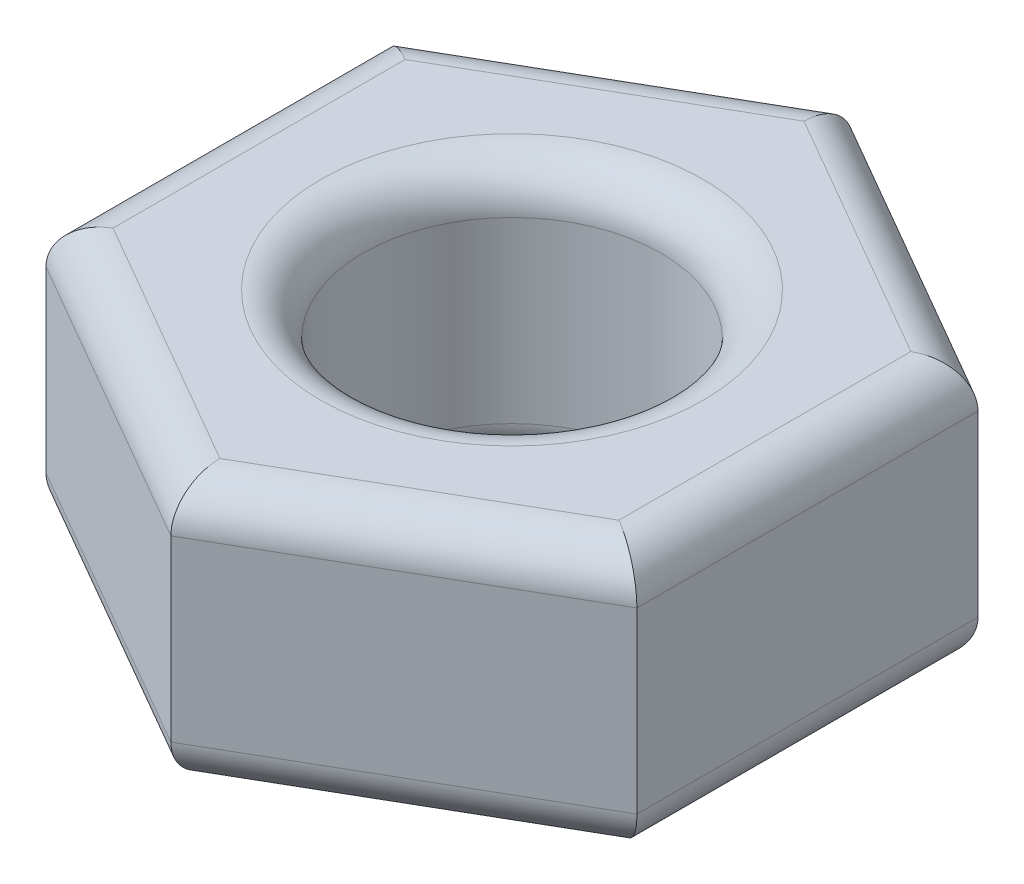
SolidWorks part; units mm, degrees
ref_plane "Front Plane" through (0, 0, 0) normal (0, 0, 1) x (1, 0, 0)
ref_plane "Top Plane" through (0, 0, 0) normal (0, 1, 0) x (1, 0, 0)
ref_plane "Right Plane" through (0, 0, 0) normal (1, 0, 0) x (0, 0, -1)
sketch "Sketch1" plane through (0, 0, 0) normal (0, 1, 0) x (1, 0, 0)
  line L0 (0, 4.0126) -> (0, -4.0126) construction
  line L1 (0, -4.0126) -> (3.475, -2.0063)
  line L2 (3.475, -2.0063) -> (3.475, 2.0063)
  line L3 (3.475, 2.0063) -> (0, 4.0126)
  line L4 (0, 4.0126) -> (-3.475, 2.0063)
  line L5 (-3.475, 2.0063) -> (-3.475, -2.0063)
  line L6 (-3.475, -2.0063) -> (0, -4.0126)
  circle A0 centre (0, 0) radius 3.475 construction
  circle A1 centre (0, 0) radius 1.75
  dimension "D2" = 3.5
  dimension "D1" = 6.95
extrude "Boss-Extrude2" add sketch "Sketch1" along normal blind 3.1
fillet "Fillet1" radius 0.5 14 edges at (1.7375, 3.1, -3.0094) (-1.7375, 3.1, -3.0094) (-3.475, 3.1, 0) (-1.7375, 3.1, 3.0094) (1.7375, 3.1, 3.0094) (3.475, 3.1, 0) (0, 3.1, 1.75) (0, 0, 1.75) (1.7375, 0, 3.0094) (3.475, 0, 0) (1.7375, 0, -3.0094) (-1.7375, 0, -3.0094) (-3.475, 0, 0) (-1.7375, 0, 3.0094)
